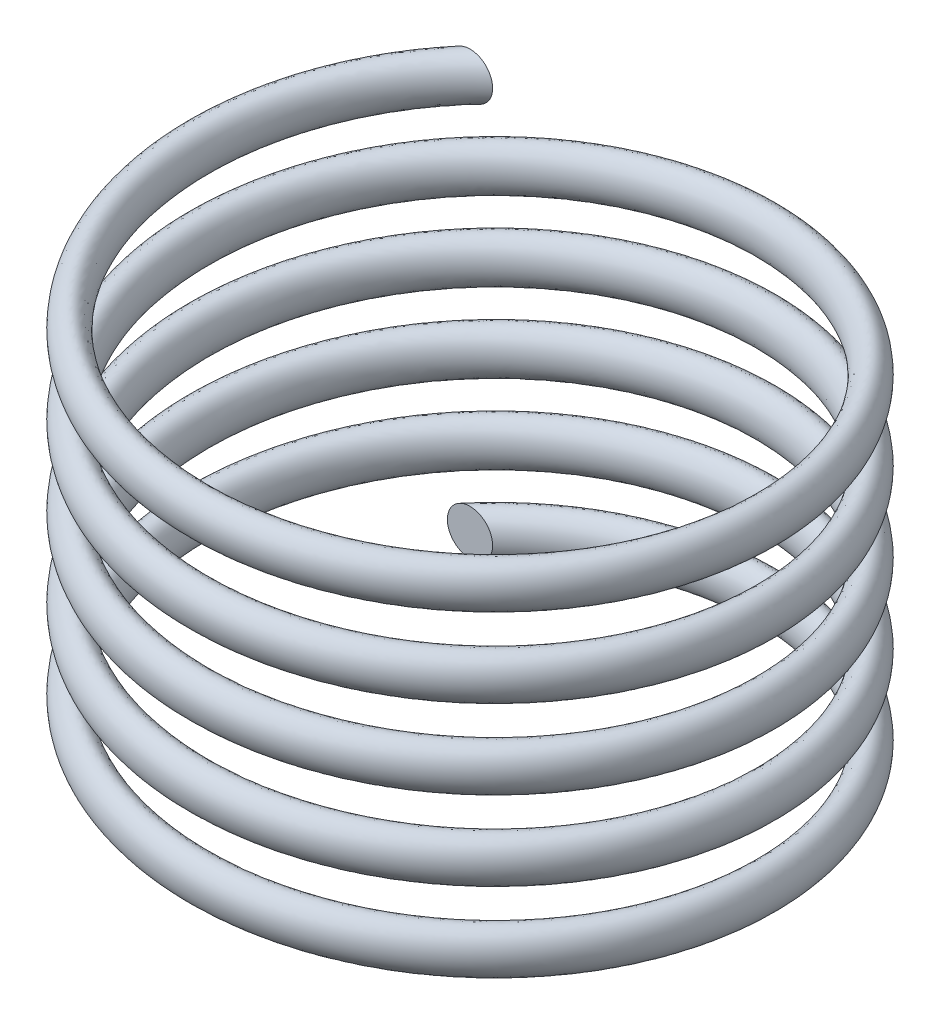
SolidWorks part; units mm, degrees
ref_plane "Front Plane" through (0, 0, 0) normal (0, 0, 1) x (1, 0, 0)
ref_plane "Top Plane" through (0, 0, 0) normal (0, 1, 0) x (1, 0, 0)
ref_plane "Right Plane" through (0, 0, 0) normal (1, 0, 0) x (0, 0, -1)
sketch "Sketch2" plane through (0, 0, 0) normal (0, 1, 0) x (1, 0, 0)
  circle A0 centre (0, 0) radius 25
curve "Helix/Spiral1" pitch 7 height 35 turns 5
ref_plane "Plane1" through (0, 0, -17.6777) normal (0, 0, 1) x (1, 0, 0)
sketch "Sketch3" plane through (0, 0, -17.6777) normal (0, 0, 1) x (1, 0, 0)
  circle A0 centre (-17.6777, 0) radius 2
  spline S0 degree 3 poles (-17.6777, 0) (-16.0005, 0.1057) (-12.1426, 0.3183) (-5.3876, 0.6363) (1.8081, 0.9546) (8.8561, 1.2727) (15.187, 1.5909) (20.2875, 1.9091) (23.7443, 2.2273) (25.2776, 2.5455) (24.763, 2.8636) (22.2423, 3.1818) (17.9196, 3.5) (12.1452, 3.8182) (5.3869, 4.1364) (-1.8079, 4.4545) (-8.8562, 4.7727) (-15.187, 5.0909) (-20.2875, 5.4091) (-23.7443, 5.7273) (-25.2776, 6.0455) (-24.763, 6.3636) (-22.2423, 6.6818) (-17.9196, 7) (-12.1452, 7.3182) (-5.3869, 7.6364) (1.8079, 7.9545) (8.8562, 8.2727) (15.187, 8.5909) (20.2875, 8.9091) (23.7443, 9.2273) (25.2776, 9.5455) (24.763, 9.8636) (22.2423, 10.1818) (17.9196, 10.5) (12.1452, 10.8182) (5.3869, 11.1364) (-1.8079, 11.4545) (-8.8562, 11.7727) (-15.187, 12.0909) (-20.2875, 12.4091) (-23.7443, 12.7273) (-25.2776, 13.0455) (-24.763, 13.3636) (-22.2423, 13.6818) (-17.9196, 14) (-12.1452, 14.3182) (-5.3869, 14.6364) (1.8079, 14.9545) (8.8562, 15.2727) (15.187, 15.5909) (20.2875, 15.9091) (23.7443, 16.2273) (25.2776, 16.5455) (24.763, 16.8636) (22.2423, 17.1818) (17.9196, 17.5) (12.1452, 17.8182) (5.3869, 18.1364) (-1.8079, 18.4545) (-8.8562, 18.7727) (-15.187, 19.0909) (-20.2875, 19.4091) (-23.7443, 19.7273) (-25.2776, 20.0455) (-24.763, 20.3636) (-22.2423, 20.6818) (-17.9196, 21) (-12.1452, 21.3182) (-5.3869, 21.6364) (1.8079, 21.9545) (8.8562, 22.2727) (15.187, 22.5909) (20.2875, 22.9091) (23.7443, 23.2273) (25.2776, 23.5455) (24.763, 23.8636) (22.2423, 24.1818) (17.9196, 24.5) (12.1452, 24.8182) (5.3869, 25.1364) (-1.8079, 25.4545) (-8.8562, 25.7727) (-15.187, 26.0909) (-20.2875, 26.4091) (-23.7443, 26.7273) (-25.2776, 27.0455) (-24.763, 27.3636) (-22.2423, 27.6818) (-17.9196, 28) (-12.1452, 28.3182) (-5.3869, 28.6364) (1.8079, 28.9545) (8.8562, 29.2727) (15.187, 29.5909) (20.2875, 29.9091) (23.7443, 30.2273) (25.2776, 30.5455) (24.763, 30.8636) (22.2423, 31.1818) (17.9196, 31.5) (12.1452, 31.8182) (5.3869, 32.1364) (-1.8079, 32.4545) (-8.8562, 32.7727) (-15.187, 33.0909) (-20.2875, 33.4091) (-23.7443, 33.7273) (-25.2778, 34.0454) (-24.7623, 34.3637) (-22.2449, 34.6817) (-19.3549, 34.8943) (-17.6777, 35) knots 0 0 0 0 0.009091 0.018182 0.027273 0.036364 0.045455 0.054545 0.063636 0.072727 0.081818 0.090909 0.1 0.109091 0.118182 0.127273 0.136364 0.145455 0.154545 0.163636 0.172727 0.181818 0.190909 0.2 0.209091 0.218182 0.227273 0.236364 0.245455 0.254545 0.263636 0.272727 0.281818 0.290909 0.3 0.309091 0.318182 0.327273 0.336364 0.345455 0.354545 0.363636 0.372727 0.381818 0.390909 0.4 0.409091 0.418182 0.427273 0.436364 0.445455 0.454545 0.463636 0.472727 0.481818 0.490909 0.5 0.509091 0.518182 0.527273 0.536364 0.545455 0.554545 0.563636 0.572727 0.581818 0.590909 0.6 0.609091 0.618182 0.627273 0.636364 0.645455 0.654545 0.663636 0.672727 0.681818 0.690909 0.7 0.709091 0.718182 0.727273 0.736364 0.745455 0.754545 0.763636 0.772727 0.781818 0.790909 0.8 0.809091 0.818182 0.827273 0.836364 0.845455 0.854545 0.863636 0.872727 0.881818 0.890909 0.9 0.909091 0.918182 0.927273 0.936364 0.945455 0.954545 0.963636 0.972727 0.981818 0.990909 1 1 1 1 construction
sweep "Sweep1" add profiles "Sketch3" path "Helix/Spiral1"
sketch "Sketch4" plane through (0, 0, 0) normal (0, 1, 0) x (1, 0, 0)
  circle A0 centre (0, 0) radius 25
